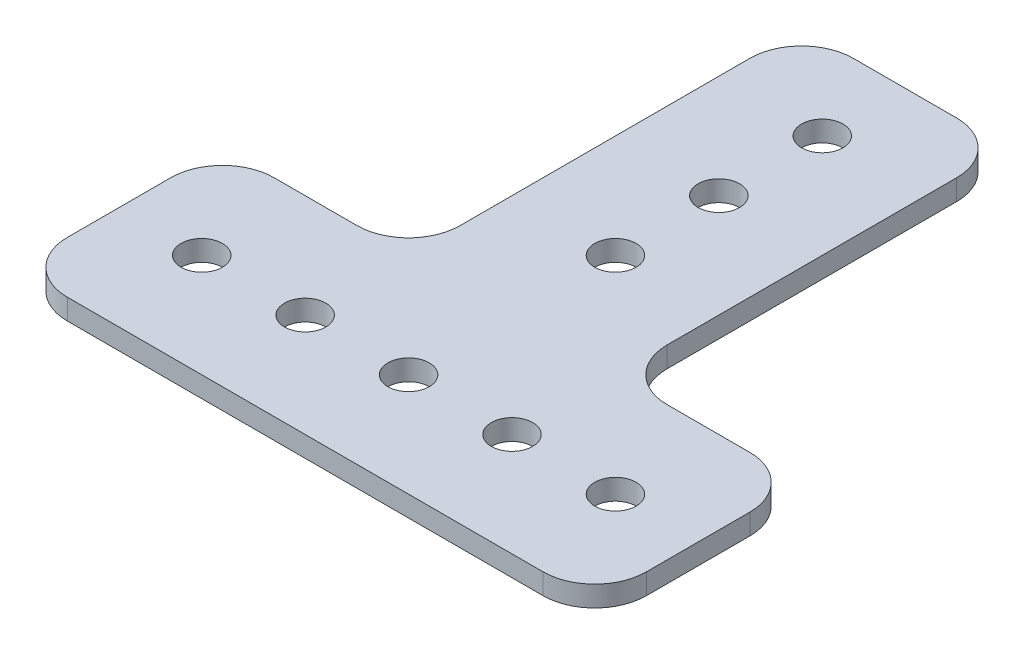
SolidWorks part; units mm, degrees
material "Hexcel AS4C (3000 Filaments)"
ref_plane "前基準面" through (0, 0, 0) normal (0, 0, 1) x (1, 0, 0)
ref_plane "上基準面" through (0, 0, 0) normal (0, 1, 0) x (1, 0, 0)
ref_plane "右基準面" through (0, 0, 0) normal (1, 0, 0) x (0, 0, -1)
sketch "草圖1" plane through (0, 0, 0) normal (0, 1, 0) x (1, 0, 0)
  line L0 (0, 0) -> (18, 0)
  line L1 (18, 0) -> (18, 38)
  line L2 (18, 38) -> (38, 38)
  line L3 (38, 38) -> (38, 0)
  line L4 (38, 0) -> (56, 0)
  line L5 (56, 0) -> (56, -20)
  line L6 (56, -20) -> (0, -20)
  line L7 (0, -20) -> (0, 0)
  line L8 (0, -10) -> (8, -10) construction
  line L9 (8, -10) -> (28, -10) construction
  line L10 (28, -10) -> (48, -10) construction
  line L11 (28, 38) -> (28, 30) construction
  line L12 (28, -10) -> (28, 10) construction
  line L13 (28, 10) -> (28, 30) construction
  line L14 (48, -10) -> (56, -10) construction
  dimension "D1" = 20
  dimension "D2" = 20
  dimension "D3" = 8
  dimension "D4" = 20
extrude "填料-伸長1" add sketch "草圖1" along normal blind 2
hole_wizard "Ø4.0 (4) 直徑孔1" positions "草圖6" profile "草圖5" hole size "Ø4.0" standard "ISO" end condition through all
sketch "草圖6" plane through (0, 0, 0) normal (0, -1, 0) x (-1, 0, 0)
  point P0 (-28, 30)
  point P3 (-28, 10)
  point P6 (-28, -10)
  point P9 (-8, -10)
  point P12 (-48, -10)
sketch "草圖5" plane through (28, 0, -30) normal (1, 0, 0) x (0, 0, -1)
  line L0 (0, 0) -> (0, 2)
  line L1 (0, 2) -> (2, 2)
  line L2 (2, 2) -> (2, 0)
  line L5 (2, 0) -> (0, 0)
  line L11 (0, -6.35) -> (0, 107.95) construction
  dimension "貫穿孔直徑" = 4
  dimension "貫穿孔深度" = 2
fillet "圓角1" radius 5 6 edges at (18, 1, -38) (38, 1, -38) (56, 1, 0) (56, 1, 20) (0, 1, 20) (0, 1, 0)
fillet "圓角2" radius 5 2 edges at (18, 1, 0) (38, 1, 0)
hole_wizard "Ø4.0 (4) 直徑孔2" positions "草圖7" profile "草圖8" hole size "Ø4.0" standard "ISO" end condition through all
sketch "草圖7" plane through (0, 0, 0) normal (0, -1, 0) x (-1, 0, 0)
  line L0 (-28, 10) -> (-28, 30) construction
  line L1 (-8, -10) -> (-28, -10) construction
  line L2 (-28, -10) -> (-48, -10) construction
  point P0 (-38, -10)
  point P2 (-18, -10)
  point P4 (-28, 20)
sketch "草圖8" plane through (38, 0, 10) normal (1, 0, 0) x (0, 0, -1)
  line L0 (0, 0) -> (0, 2)
  line L1 (0, 2) -> (2, 2)
  line L2 (2, 2) -> (2, 0)
  line L5 (2, 0) -> (0, 0)
  line L11 (0, -6.35) -> (0, 107.95) construction
  dimension "貫穿孔直徑" = 4
  dimension "貫穿孔深度" = 2
